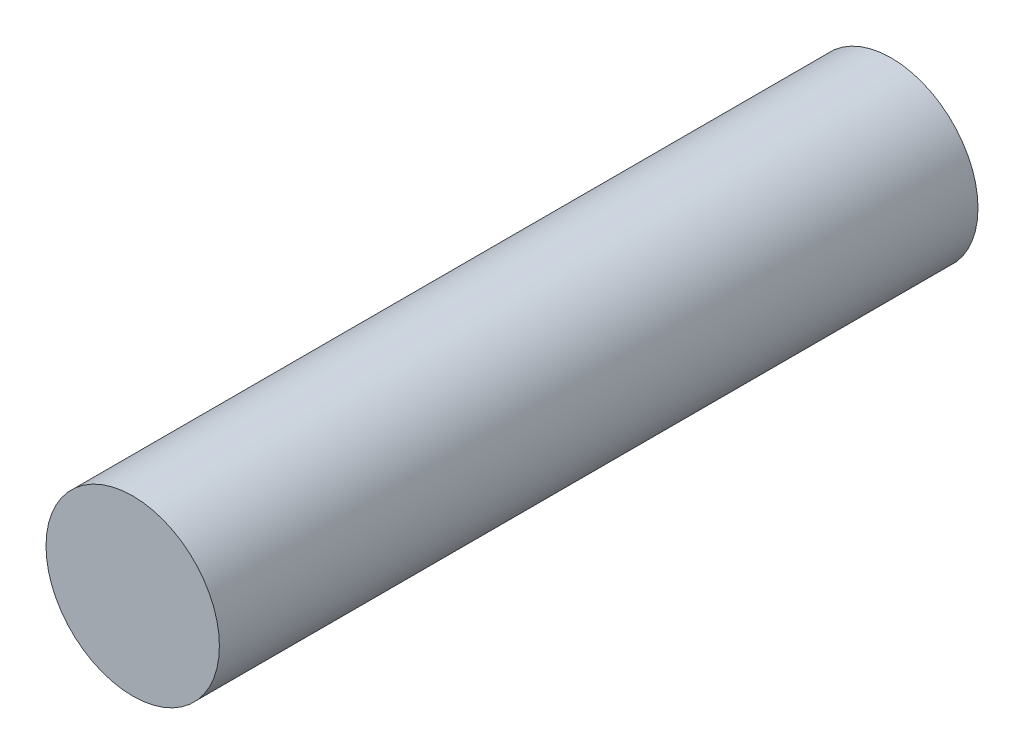
SolidWorks part; units mm, degrees
ref_plane "Ebene vorne" through (0, 0, 0) normal (0, 0, 1) x (1, 0, 0)
ref_plane "Ebene oben" through (0, 0, 0) normal (0, 1, 0) x (1, 0, 0)
ref_plane "Ebene rechts" through (0, 0, 0) normal (1, 0, 0) x (0, 0, -1)
sketch "Skizze1" plane through (0, 0, 0) normal (0, 0, 1) x (1, 0, 0)
  circle A0 centre (0, 0) radius 4
  dimension "D1" = 8
extrude "Aufsatz-Linear austragen1" add sketch "Skizze1" along normal blind 35
